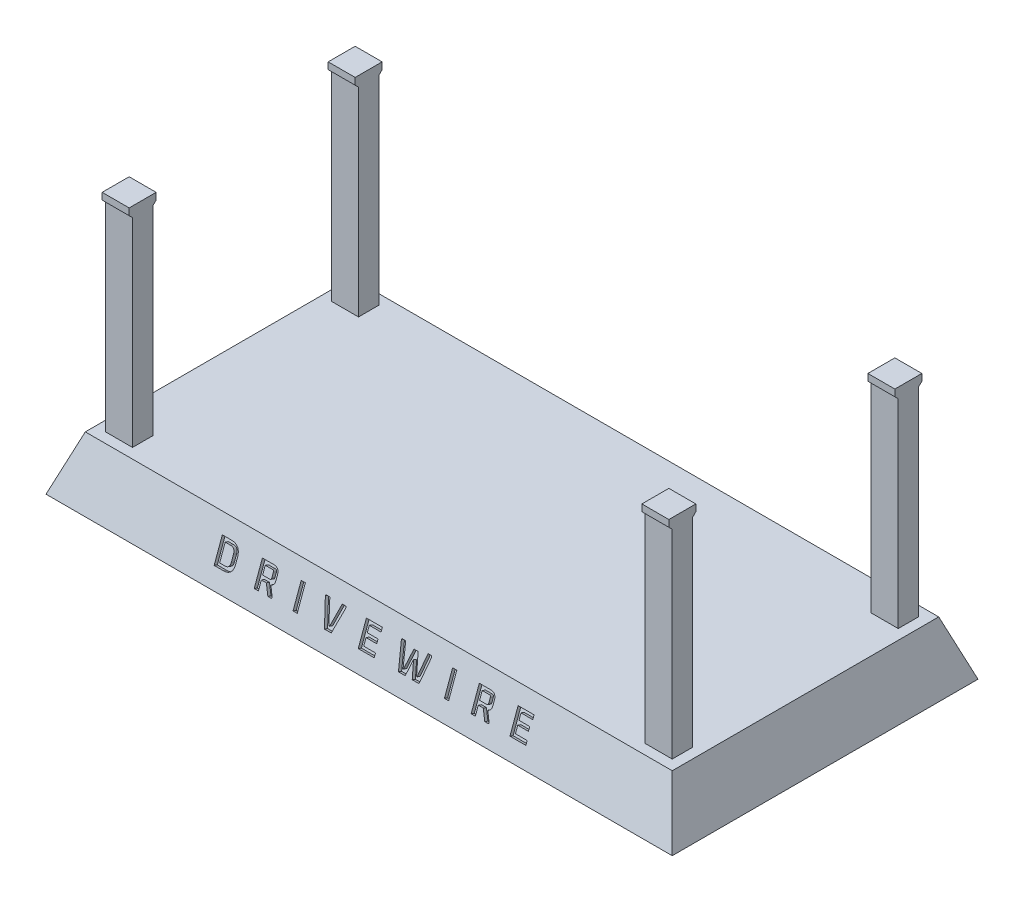
SolidWorks part; units mm, degrees
ref_plane "Front Plane" through (0, 0, 0) normal (0, 0, 1) x (1, 0, 0)
ref_plane "Top Plane" through (0, 0, 0) normal (0, 1, 0) x (1, 0, 0)
ref_plane "Right Plane" through (0, 0, 0) normal (1, 0, 0) x (0, 0, -1)
sketch "Sketch1" plane through (0, 0, 0) normal (0, 1, 0) x (1, 0, 0)
  line L1 (-87, -39.5) -> (87, -39.5)
  line L2 (-87, -39.5) -> (-87, 39.5)
  line L3 (-87, 39.5) -> (87, 39.5)
  line L4 (87, -39.5) -> (87, 39.5)
  line L5 (-87, -39.5) -> (87, 39.5) construction
  line L6 (-87, 39.5) -> (87, -39.5) construction
  point P0 (0, 0)
  dimension "D1" = 174
  dimension "D2" = 79
extrude "Boss-Extrude1" add sketch "Sketch1" against normal blind 16 draft 20 draft outward yes
sketch "Sketch2" plane through (0, 12.6951, 34.8794) normal (0, 0.342, 0.9397) x (1, 0, 0)
  text T0 "D  R  I  V  E  W  I  R  E" font "Oxanium SemiBold" height in points 26
extrude "Cut-Extrude1" cut sketch "Sketch2" against normal blind 1
sketch "Sketch3" plane through (0, 0, 0) normal (0, 1, 0) x (1, 0, 0)
  line L0 (-87, 39.5) -> (-87, -39.5) construction
  line L1 (-84, -36.5) -> (-76, -36.5)
  line L2 (-84, -36.5) -> (-84, -30.5)
  line L3 (-84, -30.5) -> (-76, -30.5)
  line L4 (-76, -36.5) -> (-76, -30.5)
  line L5 (-84, -36.5) -> (-76, -30.5) construction
  line L6 (-84, -30.5) -> (-76, -36.5) construction
  line L7 (-87, -39.5) -> (87, -39.5) construction
  line L12 (-84, 30.5) -> (-76, 36.5) construction
  line L13 (-84, 36.5) -> (-76, 30.5) construction
  line L14 (-76, 36.5) -> (-76, 30.5)
  line L15 (-84, 30.5) -> (-76, 30.5)
  line L16 (-84, 36.5) -> (-84, 30.5)
  line L17 (-84, 36.5) -> (-76, 36.5)
  line L18 (84, -30.5) -> (76, -36.5) construction
  line L19 (84, -36.5) -> (76, -30.5) construction
  line L20 (76, -36.5) -> (76, -30.5)
  line L21 (84, -30.5) -> (76, -30.5)
  line L22 (84, -36.5) -> (84, -30.5)
  line L23 (84, -36.5) -> (76, -36.5)
  line L24 (84, 36.5) -> (76, 30.5) construction
  line L25 (84, 30.5) -> (76, 36.5) construction
  line L26 (84, 36.5) -> (76, 36.5)
  line L27 (84, 36.5) -> (84, 30.5)
  line L28 (84, 30.5) -> (76, 30.5)
  line L29 (76, 36.5) -> (76, 30.5)
  point P0 (-80, -33.5)
  point P21 (-80, 33.5)
  point P26 (80, -33.5)
  point P31 (80, 33.5)
  dimension "D1" = 6
  dimension "D2" = 8
  dimension "D3" = 3
  dimension "D4" = 3
extrude "Boss-Extrude2" add sketch "Sketch3" along normal blind 60
sketch "Sketch4" plane through (0, 60, 0) normal (0, 1, 0) x (1, 0, 0)
  line L6 (-84, 29.5) -> (-76, 37.5) construction
  line L7 (-84, -37.5) -> (-76, -37.5)
  line L8 (-84, -37.5) -> (-84, -29.5)
  line L9 (-84, -29.5) -> (-76, -29.5)
  line L10 (-76, -37.5) -> (-76, -29.5)
  line L11 (-84, -37.5) -> (-76, -29.5) construction
  line L12 (-84, -29.5) -> (-76, -37.5) construction
  line L13 (-84, 37.5) -> (-76, 29.5) construction
  line L14 (-76, 37.5) -> (-76, 29.5)
  line L15 (-84, 29.5) -> (-76, 29.5)
  line L16 (-84, 37.5) -> (-84, 29.5)
  line L17 (-84, 37.5) -> (-76, 37.5)
  line L18 (84, -29.5) -> (76, -37.5) construction
  line L19 (84, -37.5) -> (76, -29.5) construction
  line L20 (76, -37.5) -> (76, -29.5)
  line L21 (84, -29.5) -> (76, -29.5)
  line L22 (84, -37.5) -> (84, -29.5)
  line L23 (84, -37.5) -> (76, -37.5)
  line L24 (84, 37.5) -> (76, 29.5) construction
  line L25 (84, 29.5) -> (76, 37.5) construction
  line L26 (84, 37.5) -> (76, 37.5)
  line L27 (84, 37.5) -> (84, 29.5)
  line L28 (84, 29.5) -> (76, 29.5)
  line L29 (76, 37.5) -> (76, 29.5)
  point P12 (-80, -33.5)
  point P21 (-80, 33.6877)
  point P26 (80, -33.6877)
  point P31 (80, 33.6877)
  dimension "D1" = 8
  dimension "D2" = 8
  dimension "D3" = 1
  dimension "D4" = 1
  dimension "D5" = 1
  dimension "D6" = 1
extrude "Boss-Extrude4" add sketch "Sketch4" along normal blind 2
ref_plane "Plane2" through (84, 60, 36.5) normal (1, 0, 0) x (0, 0, -1)
ref_plane "Plane3" through (84, 60, 30.5) normal (1, 0, 0) x (0, 0, -1)
sketch "Sketch10" plane through (84, 0, 0) normal (1, 0, 0) x (0, 0, -1)
  line L0 (-37.5, 60) -> (-36.5, 59)
  line L1 (-36.5, 60) -> (-36.5, 0) construction
rib "Rib12" sketch "Sketch10" sketch "Sketch10" thickness 8 extrusion direction parallel to sketch draft on no parameters "D1"=8
sketch "Sketch11" plane through (84, 60, 30.5) normal (1, 0, 0) x (0, 0, -1)
  line L0 (1, 0) -> (0, -1)
  line L1 (0, 0) -> (0, -60) construction
rib "Rib13" sketch "Sketch11" sketch "Sketch11" thickness 8 extrusion direction parallel to sketch draft on no parameters "D1"=8
sketch "Sketch12" plane through (84, 60, 30.5) normal (1, 0, 0) x (0, 0, -1)
  line L0 (60, 0) -> (61, -1)
  line L1 (61, 0) -> (61, -60) construction
rib "Rib14" sketch "Sketch12" sketch "Sketch12" thickness 8 extrusion direction parallel to sketch draft on no parameters "D1"=8
sketch "Sketch13" plane through (84, 60, 36.5) normal (1, 0, 0) x (0, 0, -1)
  line L0 (74, 0) -> (73, -1)
  line L1 (73, 0) -> (73, -60) construction
rib "Rib15" sketch "Sketch13" sketch "Sketch13" thickness 8 extrusion direction parallel to sketch draft on no parameters "D1"=8
ref_plane "Plane4" through (-84, 0, 0) normal (-1, 0, 0) x (0, 0, 1)
sketch "Sketch14" plane through (-84, 0, 0) normal (-1, 0, 0) x (0, 0, 1)
  line L0 (-37.5, 60) -> (-36.5, 59)
rib "Rib16" sketch "Sketch14" sketch "Sketch14" thickness 8 extrusion direction parallel to sketch draft on no parameters "D1"=8
sketch "Sketch15" plane through (-84, 0, 0) normal (-1, 0, 0) x (0, 0, 1)
  line L0 (-29.5, 60) -> (-30.5, 59)
rib "Rib17" sketch "Sketch15" sketch "Sketch15" thickness 8 extrusion direction parallel to sketch draft on no parameters "D1"=8
sketch "Sketch16" plane through (-84, 0, 0) normal (-1, 0, 0) x (0, 0, 1)
  line L0 (29.5, 60) -> (30.5, 59)
rib "Rib18" sketch "Sketch16" sketch "Sketch16" thickness 8 extrusion direction parallel to sketch draft on no parameters "D1"=8
sketch "Sketch17" plane through (-84, 0, 0) normal (-1, 0, 0) x (0, 0, 1)
  line L0 (37.5, 60) -> (36.5, 59)
  line L1 (36.5, 60) -> (36.5, 0) construction
  line L2 (37.5, 60) -> (36.5, 59) construction
rib "Rib19" sketch "Sketch17" sketch "Sketch17" thickness 8 extrusion direction parallel to sketch draft on no parameters "D1"=8
